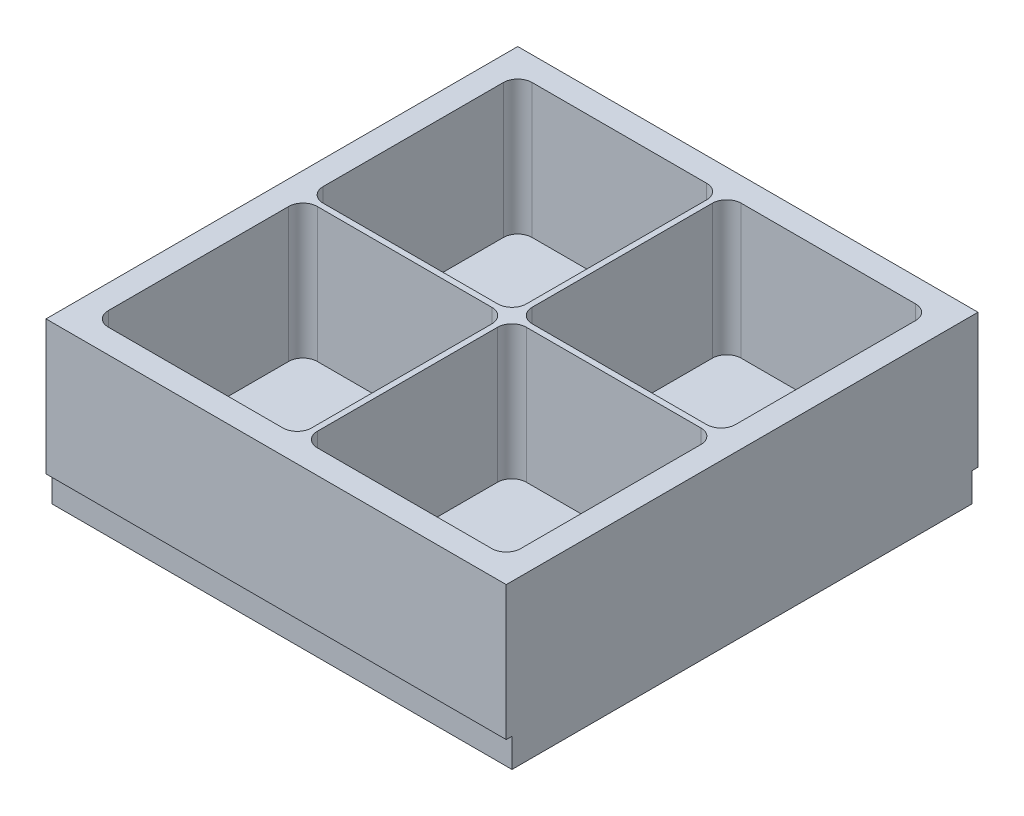
SolidWorks part; units mm, degrees
material "6061-T6 (SS)"
ref_plane "Front Plane" through (0, 0, 0) normal (0, 0, 1) x (1, 0, 0)
ref_plane "Top Plane" through (0, 0, 0) normal (0, 1, 0) x (1, 0, 0)
ref_plane "Right Plane" through (0, 0, 0) normal (1, 0, 0) x (0, 0, -1)
sketch "Sketch1" plane through (0, 0, 0) normal (0, 1, 0) x (1, 0, 0)
  line L0 (0, -49.2) -> (0, 49.2) construction
  line L1 (-48, -49.2) -> (48, -49.2)
  line L2 (-48, -49.2) -> (-48, 49.2)
  line L3 (-48, 49.2) -> (48, 49.2)
  line L4 (48, -49.2) -> (48, 49.2)
  line L5 (-48, -49.2) -> (48, 49.2) construction
  line L6 (-48, 49.2) -> (48, -49.2) construction
  line L7 (-48, 0) -> (48, 0) construction
  line L8 (-43, -44.2) -> (-43, -0.6)
  line L9 (-43, 44.2) -> (-0.6, 44.2)
  line L10 (43, -44.2) -> (43, -0.6)
  line L11 (-43, -44.2) -> (-0.6, -44.2)
  line L12 (0.6, -0.615) -> (0.6, 0.615) construction
  line L13 (-43, -0.6) -> (43, -0.6) construction
  line L14 (-0.6, -0.615) -> (-0.6, 0.615) construction
  line L15 (-43, 0.6) -> (43, 0.6) construction
  line L16 (0.6, 44.2) -> (43, 44.2)
  line L17 (-0.6, -49.2) -> (-0.6, 49.2) construction
  line L18 (0.6, -49.2) -> (0.6, 49.2) construction
  line L19 (-43, 0.6) -> (-43, 44.2)
  line L20 (-43, 44.2) -> (43, 44.2) construction
  line L21 (-48, -0.6) -> (48, -0.6) construction
  line L22 (0.6, -44.2) -> (43, -44.2)
  line L23 (-43, -44.2) -> (-43, 44.2) construction
  line L24 (-48, 0.6) -> (48, 0.6) construction
  line L25 (43, 0.6) -> (43, 44.2)
  line L26 (-43, -44.2) -> (43, -44.2) construction
  line L27 (-0.6, 0.615) -> (-0.6, 44.2)
  line L28 (43, -44.2) -> (43, 44.2) construction
  line L29 (-0.6, -0.615) -> (-0.6, -44.2)
  line L30 (0.6, 0.615) -> (0.6, 44.2)
  line L31 (0.6, -0.615) -> (0.6, -44.2)
  line L32 (-43, 0.6) -> (-0.6, 0.615)
  line L33 (-43, -0.6) -> (-0.6, -0.615)
  line L34 (0.6, 0.615) -> (43, 0.6)
  line L35 (0.6, -0.615) -> (43, -0.6)
  point P0 (0, 0)
  dimension "D1" = 98.4
  dimension "D2" = 96
  dimension "D3" = 5
  dimension "D4" = 0.6
  dimension "D5" = 0.6
extrude "Boss-Extrude1" add sketch "Sketch1" along normal blind 28
fillet "Fillet1" radius 3 16 edges at (-43, 14, 44.2) (0.6, 14, 44.2) (-0.6, 14, 44.2) (43, 14, 44.2) (43, 14, -0.6) (43, 14, -44.2) (0.6, 14, -44.2) (-0.6, 14, -44.2) (-43, 14, -0.6) (-43, 14, -44.2) (0.6, 14, 0.615) (-0.6, 14, 0.615) (0.6, 14, -0.615) (-0.6, 14, -0.615) (43, 14, 0.6) (-43, 14, 0.6)
sketch "Sketch2" plane through (0, 0, 0) normal (0, -1, 0) x (1, 0, 0)
  line L1 (48, -48) -> (-48, -48)
  line L2 (48, -48) -> (48, 48)
  line L3 (48, 48) -> (-48, 48)
  line L4 (-48, -48) -> (-48, 48)
  line L5 (48, -48) -> (-48, 48) construction
  line L6 (48, 48) -> (-48, -48) construction
  point P0 (0, 0)
  dimension "D1" = 96
extrude "Boss-Extrude2" add sketch "Sketch2" along normal blind 6
sketch "Sketch4" plane through (0, -6, 0) normal (0, -1, 0) x (1, 0, 0)
  line L1 (47.945, -45.085) -> (-47.945, -45.085) construction
  line L2 (47.945, -45.085) -> (47.945, 45.085) construction
  line L3 (47.945, 45.085) -> (-47.945, 45.085) construction
  line L4 (-47.945, -45.085) -> (-47.945, 45.085) construction
  line L5 (47.945, -45.085) -> (-47.945, 45.085) construction
  line L6 (47.945, 45.085) -> (-47.945, -45.085) construction
  circle A0 centre (42.865, -40.005) radius 1.1305
  circle A1 centre (-42.865, -37.465) radius 1.1305
  circle A2 centre (42.865, 40.005) radius 1.1305
  circle A3 centre (-42.865, 36.195) radius 1.1305
  point P0 (0, 0)
  dimension "D5" = 2.261
  dimension "D8" = 2.261
  dimension "D11" = 2.261
  dimension "D13" = 2.261
  dimension "D1" = 90.17
  dimension "D2" = 95.89
  dimension "D3" = 5.08
  dimension "D4" = 5.08
  dimension "D6" = 90.81
  dimension "D7" = 7.62
  dimension "D9" = 81.28
  dimension "D10" = 90.81
  dimension "D12" = 5.08
  dimension "D14" = 5.08
extrude "Cut-Extrude2" cut sketch "Sketch4" against normal blind 4.7
sketch "Sketch6" plane through (0, 0, 0) normal (0, 1, 0) x (1, 0, 0)
  line L0 (-21.8, 44.2) -> (-21.8, -44.2) construction
  line L1 (-3.6, 44.2) -> (-40, 44.2) construction
  line L2 (-40, -44.2) -> (-3.6, -44.2) construction
  line L3 (21.8, -44.2) -> (21.8, 44.2) construction
  line L6 (45.8197, 23.4167) -> (43, 22.4005)
  line L7 (3.6, -44.2) -> (40, -44.2) construction
  line L8 (40, 44.2) -> (3.6, 44.2) construction
  line L9 (43, 3.6011) -> (43, 41.2) construction
  line L10 (43, 22.4005) -> (-43, 22.4005) construction
  line L11 (-43, 41.2) -> (-43, 3.6011) construction
  line L12 (-43, -22.4005) -> (43, -22.4005) construction
  line L13 (-43, -3.6011) -> (-43, -41.2) construction
  line L14 (43, -41.2) -> (43, -3.6011) construction
  line L15 (21.8, 44.2) -> (23.3024, 46.2686)
  circle A0 centre (-21.8, 22.4005) radius 5.5
  circle A1 centre (21.8, 22.4005) radius 5.5
  circle A2 centre (21.8, -22.4005) radius 5.5
  circle A3 centre (-21.8, -22.4005) radius 5.5
  dimension "D1" = 11
  dimension "D2" = 11
  dimension "D3" = 11
  dimension "D4" = 11
extrude "Cut-Extrude3" cut sketch "Sketch6" against normal through all contours A3 | A2 | A1 | A0
